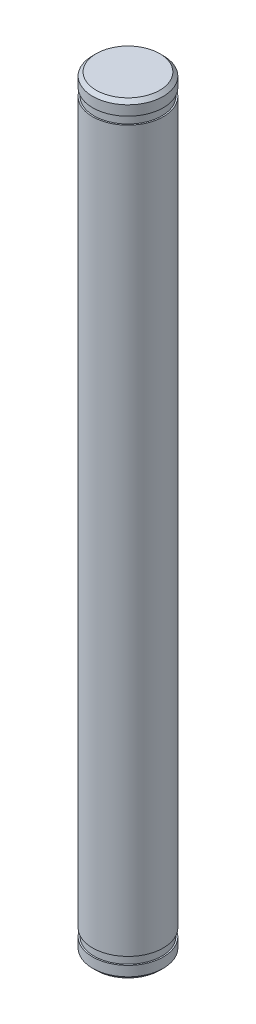
SolidWorks part; units mm, degrees
ref_plane "前视基准面" through (0, 0, 0) normal (0, 0, 1) x (1, 0, 0)
ref_plane "上视基准面" through (0, 0, 0) normal (0, 1, 0) x (1, 0, 0)
ref_plane "右视基准面" through (0, 0, 0) normal (1, 0, 0) x (0, 0, -1)
other "Configuration Table"
sketch "草图1" plane through (0, 0, 0) normal (0, 1, 0) x (1, 0, 0)
  circle A0 centre (0, 0) radius 5
  dimension "D1" = 10
extrude "凸台-拉伸1" add sketch "草图1" along normal blind 108
chamfer "倒角1" distance 0.5 angle 45 2 edges at (0, 0, 5) (0, 108, 5)
ref_plane "基准面1" through (0, 54, 0) normal (0, 1, 0) x (1, 0, 0)
sketch "草图2" plane through (0, 108, 0) normal (0, 1, 0) x (1, 0, 0)
  circle A0 centre (0, 0) radius 5 construction
  circle A1 centre (0, 0) radius 5
  circle A2 centre (0, 0) radius 4.8
  dimension "D1" = 9.6
extrude "切除-拉伸1" cut sketch "草图2" along normal blind 1.1 from offset 3 offset against normal yes
mirror "镜向1" about plane through (0, 54, 0) normal (0, 1, 0) of "切除-拉伸1"
